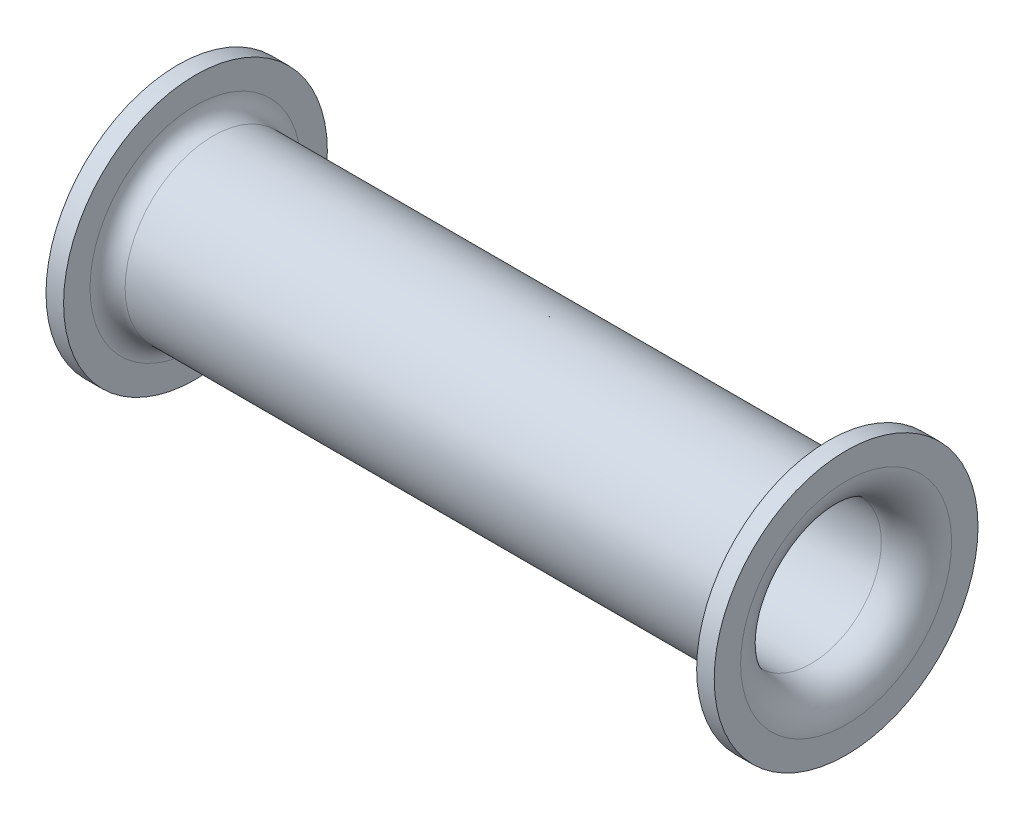
SolidWorks part; units mm, degrees
revolve "Base-Revolve" add sketch "Sketch1" angle 360 about L0
sketch "Sketch1" plane through (0, 0, 0) normal (0, 0, 1) x (1, 0, 0)
  line L0 (-20, 0) -> (20, 0) construction
  line L2 (-20, 4) -> (20, 4)
  line L3 (-20, 4) -> (-20, 5)
  line L4 (-20, 5) -> (20, 5)
  line L5 (20, 4) -> (20, 5)
  dimension "Length" = 40
  dimension "WallThickness" = 1
  dimension "Diameter" = 10
  dimension "D1" = 20
revolve "Cut-for-GripLength" cut sketch "Sketch2" angle 360 about L0
sketch "Sketch2" plane through (0, 0, 0) normal (0, 0, 1) x (1, 0, 0)
  line L0 (-30, 0) -> (30, 0) construction
  line L1 (-20, 5) -> (-20, -5) construction
  line L2 (-20, 0) -> (-17, 0)
  line L3 (-20, 0) -> (-20, 6)
  line L4 (-20, 6) -> (-17, 6)
  line L5 (-17, 0) -> (-17, 6)
  line L6 (17, 0) -> (20, 0)
  line L7 (17, 0) -> (17, 6)
  line L8 (17, 6) -> (20, 6)
  line L9 (20, 0) -> (20, 6)
  line L10 (20, -5) -> (20, 5) construction
  point P15 (-18, 6)
  point P16 (18, 6)
  dimension "D4" = 12
  dimension "GripLength" = 36
  dimension "D1" = 18
  dimension "CutByR" = 1
  dimension "D2" = 1
  dimension "D3" = 34
ref_plane "Plane1" through (0, 0, 0) normal (0, 0, 1) x (1, 0, 0)
ref_plane "Plane2" through (0, 0, 0) normal (0, 1, 0) x (1, 0, 0)
ref_plane "Plane3" through (0, 0, 0) normal (1, 0, 0) x (0, 0, -1)
sketch "Sketch3" plane through (0, 0, 0) normal (0, 0, 1) x (1, 0, 0)
  line L0 (17, -5) -> (17, 5) construction
  line L1 (-19, 6) -> (-19, 7.5)
  line L2 (-19, 7.5) -> (-18, 7.5)
  line L3 (-18, 7.5) -> (-18, 6)
  line L4 (-17, 5) -> (-17, -5) construction
  line L5 (-17, 5) -> (-17, 4)
  line L6 (17, 5) -> (-17, 5) construction
  line L7 (17, 4) -> (-17, 4) construction
  line L9 (-20, 0) -> (19, 0) construction
  line L10 (-20, 0) -> (20, 0) construction
  line L12 (19, 6) -> (19, 7.5)
  line L13 (19, 7.5) -> (18, 7.5)
  line L14 (18, 7.5) -> (18, 6)
  line L16 (17, 5) -> (17, 4)
  arc A0 (-18, 6) -> (-17, 5) centre (-17, 6) ccw
  arc A1 (-19, 6) -> (-17, 4) centre (-17, 6) ccw
  arc A2 (17, 5) -> (18, 6) centre (17, 6) ccw
  arc A3 (17, 4) -> (19, 6) centre (17, 6) ccw
  dimension "D3" = 1
  dimension "D1" = 1
  dimension "D2" = 1
revolve "HeadTypeA" add sketch "Sketch3" angle 360 about L9
sketch "Sketch4" plane through (0, 0, 0) normal (0, 0, 1) x (1, 0, 0)
  line L0 (-18, 5) -> (-17, 5)
  line L1 (-18, 6.5) -> (-18, 7.5)
  line L2 (0, 0) -> (0, 10) construction
  line L3 (-17, 5) -> (-17, 4)
  line L4 (-17, 4) -> (-18, 4)
  line L5 (17, 4) -> (18, 4)
  line L6 (17, 5) -> (17, 4)
  line L7 (18, 6.5) -> (18, 7.5)
  line L8 (18, 5) -> (17, 5)
  line L10 (-20, 0) -> (20, 0) construction
  line L11 (-20, 0) -> (20, 0) construction
  arc A0 (-18, 6.5) -> (-18, 5) centre (-18, 5.75) ccw
  arc A1 (-18, 7.5) -> (-18, 4) centre (-18, 5.75) ccw
  arc A2 (18, 7.5) -> (18, 4) centre (18, 5.75) cw
  arc A3 (18, 6.5) -> (18, 5) centre (18, 5.75) cw
  dimension "D4" = 1
  dimension "D1" = 15
  dimension "D2" = 1
  dimension "D3" = 10
  dimension "D5" = 34
revolve "HeadTypeB" [suppressed] add sketch "Sketch4" angle 360 about L10
equation "\"D1@Sketch1\" = \"Length@Sketch1\" / 2"
equation "\"D4@Sketch2\" = \"Diameter@Sketch1\" + 2"
equation "\"D1@Sketch3\" = \"WallThickness@Sketch1\""
equation "\"D2@Sketch3\" = \"D1@Sketch3\""
equation "\"D3@Sketch3\" = \"HeadFillet@Sketch3\""
equation "\"D4@Sketch4\" = \"WallThickness@Sketch1\""
equation "\"D1@Sketch4\" = \"HeadDia@Sketch3\""
equation "\"D2@Sketch4\" = \"HeadFillet@Sketch3\""
equation "\"D3@Sketch4\" = \"Diameter@Sketch1\""
equation "\"D1@Sketch2\" = \"GripLength@Sketch2\" / 2"
equation "\"D2@Sketch2\" = \"CutByR@Sketch2\""
equation "\"D5@Sketch4\" = \"D3@Sketch2\""
